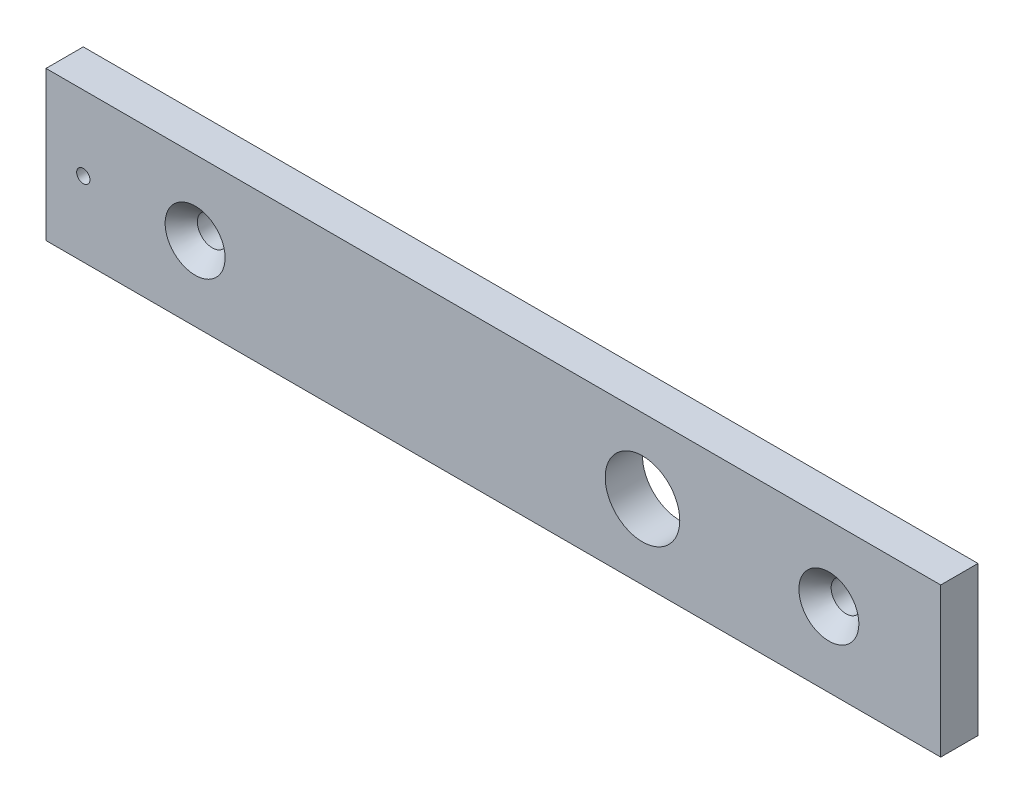
SolidWorks part; units mm, degrees
material "Brass"
ref_plane "Front Plane" through (0, 0, 0) normal (0, 0, 1) x (1, 0, 0)
ref_plane "Top Plane" through (0, 0, 0) normal (0, 1, 0) x (1, 0, 0)
ref_plane "Right Plane" through (0, 0, 0) normal (1, 0, 0) x (0, 0, -1)
sketch "Sketch1" plane through (0, 0, 0) normal (0, 0, 1) x (1, 0, 0)
  line L0 (-76.2, 12.7) -> (76.2, -12.7) construction
  line L1 (-76.2, 12.7) -> (76.2, 12.7)
  line L2 (-76.2, 12.7) -> (-76.2, -12.7)
  line L3 (-76.2, -12.7) -> (76.2, -12.7)
  line L4 (76.2, 12.7) -> (76.2, -12.7)
  dimension "D1" = 152.4
  dimension "D2" = 25.4
extrude "Extrude1" add sketch "Sketch1" along normal blind 6.35
hole_wizard "#4-40 Tapped Hole2" positions "3DSketch2" profile "Sketch10" tap size "#4-40" standard "Ansi Inch"
sketch3d "3DSketch2"
  line L0 (-76.2, 12.7, 6.35) -> (-76.2, -12.7, 6.35) construction
  line L1 (-76.2, -12.7, 6.35) -> (76.2, -12.7, 6.35) construction
  point P0 (-69.85, 0, 6.35)
  dimension "D1" = 6.35
  dimension "D2" = 12.7
sketch "Sketch10" plane through (-69.85, 0, 6.35) normal (1, 0, 0) x (0, -1, 0)
  line L0 (0, 0) -> (0, 3.9812)
  line L1 (0, 3.9812) -> (1.1303, 3.302)
  line L2 (1.1303, 3.302) -> (1.1303, 0)
  line L5 (1.1303, 0) -> (0, 0)
  line L10 (0, 3.9812) -> (-1.1303, 3.302) construction
  line L11 (0, -6.35) -> (0, 107.95) construction
  dimension "Tap Drill Dia." = 2.2606
  dimension "Tap Drill Depth" = 3.302
  dimension "Drill Angle" = 118
cosmetic thread "Hole Thread3" parameters "D1"=3.302, "D2"=2.8448
hole_wizard "1/2 (0.5) Diameter Hole1" positions "3DSketch3" profile "Sketch13" hole size "1/2" standard "Ansi Inch" end condition through all
sketch3d "3DSketch3"
  line L0 (76.2, 12.7, 6.35) -> (-76.2, 12.7, 6.35) construction
  line L1 (-76.2, 12.7, 6.35) -> (-76.2, -12.7, 6.35) construction
  point P0 (25.4, 0, 6.35)
  dimension "D1" = 12.7
  dimension "D2" = 101.6
sketch "Sketch13" plane through (25.4, 0, 6.35) normal (1, 0, 0) x (0, -1, 0)
  line L0 (0, 0) -> (0, 6.35)
  line L1 (0, 6.35) -> (6.35, 6.35)
  line L2 (6.35, 6.35) -> (6.35, 0)
  line L5 (6.35, 0) -> (0, 0)
  line L11 (0, -6.35) -> (0, 107.95) construction
  dimension "Thru Hole Dia." = 12.7
  dimension "Thru Hole Depth" = 6.35
hole_wizard "#4-40 Tapped Hole3" [suppressed] positions "3DSketch4" profile "Sketch14" tap size "#4-40" standard "Ansi Inch"
sketch3d "3DSketch4"
  point P0 (25.6107, -12.7, 3.1789)
sketch "Sketch14" plane through (25.6107, -12.7, 3.1789) normal (1, 0, 0) x (0, 0, -1)
  line L0 (0, 0) -> (0, 9.5692)
  line L1 (0, 9.5692) -> (1.1303, 8.89)
  line L2 (1.1303, 8.89) -> (1.1303, 0)
  line L5 (1.1303, 0) -> (0, 0)
  line L10 (0, 9.5692) -> (-1.1303, 8.89) construction
  line L11 (0, -6.35) -> (0, 107.95) construction
  dimension "Tap Drill Dia." = 2.2606
  dimension "Tap Drill Depth" = 8.89
  dimension "Drill Angle" = 118
cosmetic thread "Hole Thread4" [suppressed] parameters "D1"=5.588, "D2"=2.8448
hole_wizard "CSK for #10 Flat Head Socket Cap Screw2" positions "Sketch18" profile "Sketch19" countersink size "#10" standard "Ansi Inch" end condition through all
sketch "Sketch18" plane through (-2.2962, -5.3613, 6.35) normal (0, 0, 1) x (1, 0, 0)
  point P0 (59.4462, 5.3613)
sketch "Sketch19" plane through (57.15, 0, 6.35) normal (1, 0, 0) x (0, -1, 0)
  line L0 (0, 0) -> (0, 6.35)
  line L1 (0, 6.35) -> (2.5527, 6.35)
  line L2 (2.5527, 6.35) -> (2.5527, 2.938)
  line L3 (2.5527, 2.938) -> (5.1067, 0)
  line L5 (5.1067, 0) -> (0, 0)
  line L6 (-2.5527, 2.938) -> (-5.1067, 0) construction
  line L11 (0, -6.35) -> (0, 107.95) construction
  dimension "Thru Hole Dia." = 5.1054
  dimension "Thru Hole Depth" = 6.35
  dimension "Near C'Sink Dia." = 10.2133
  dimension "Near C'Sink Angle" = 82
hole_wizard "CSK for #10 Flat Head Socket Cap Screw1" positions "Sketch26" profile "Sketch27" countersink size "#10" standard "Ansi Inch" end condition through all
sketch "Sketch26" plane through (-2.2962, -5.3613, 6.35) normal (0, 0, 1) x (1, 0, 0)
  point P0 (-48.5038, 5.3613)
sketch "Sketch27" plane through (-50.8, 0, 6.35) normal (1, 0, 0) x (0, -1, 0)
  line L0 (0, 0) -> (0, 6.35)
  line L1 (0, 6.35) -> (2.5527, 6.35)
  line L2 (2.5527, 6.35) -> (2.5527, 2.938)
  line L3 (2.5527, 2.938) -> (5.1067, 0)
  line L5 (5.1067, 0) -> (0, 0)
  line L6 (-2.5527, 2.938) -> (-5.1067, 0) construction
  line L11 (0, -6.35) -> (0, 107.95) construction
  dimension "Thru Hole Dia." = 5.1054
  dimension "Thru Hole Depth" = 6.35
  dimension "Near C'Sink Dia." = 10.2133
  dimension "Near C'Sink Angle" = 82
